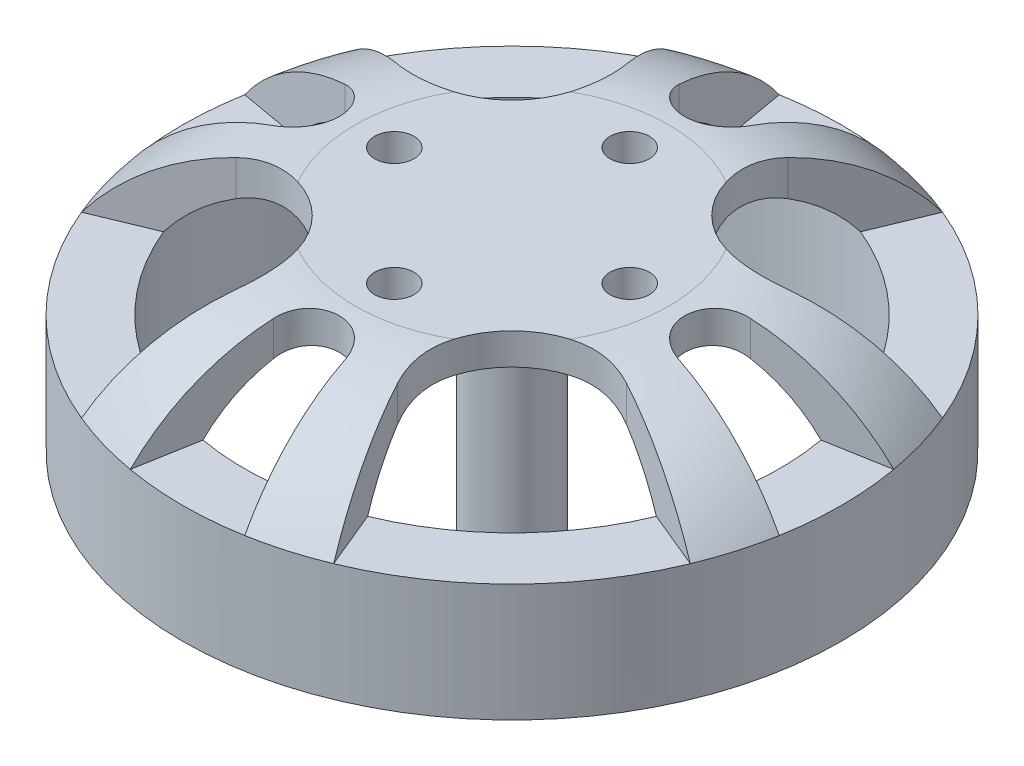
SolidWorks part; units mm, degrees
ref_plane "Front Plane" through (0, 0, 0) normal (0, 0, 1) x (1, 0, 0)
ref_plane "Top Plane" through (0, 0, 0) normal (0, 1, 0) x (1, 0, 0)
ref_plane "Right Plane" through (0, 0, 0) normal (1, 0, 0) x (0, 0, -1)
sketch "Sketch2" plane through (0, 0, 0) normal (0, 0, 1) x (1, 0, 0)
  line L0 (0, 0) -> (0, 19)
  line L1 (-21, 13.5) -> (-21, 6)
  line L2 (0, 19) -> (-10, 19)
  line L3 (0, 9.5) -> (-21, 9.5) construction
  line L4 (-21, 6) -> (-17, 6)
  line L5 (-17, 6) -> (-17, 13.5)
  line L6 (0, 0) -> (-2.5, 0)
  line L7 (-2.5, 0) -> (-2.5, 17)
  line L8 (-2.5, 17) -> (-10, 17)
  arc A0 (-10, 19) -> (-21, 13.5) centre (-10, 5.25) ccw
  arc A1 (-10, 17) -> (-17, 13.5) centre (-10, 8.25) ccw
  dimension "D1" = 21
  dimension "D2" = 19
  dimension "D3" = 7.5
  dimension "D4" = 10
  dimension "D5" = 4
  dimension "D6" = 2.5
  dimension "D7" = 2
  dimension "D8" = 4
revolve "Revolve2" add sketch "Sketch2" angle 360 about L0
hole_wizard "M3x0.5 Tapped Hole1" positions "Sketch4" profile "Sketch3" tap size "M3x0.5" standard "ANSI Metric" end condition up to next
sketch "Sketch4" plane through (0, 19, 0) normal (0, 1, 0) x (1, 0, 0)
  line L0 (0, 7.5) -> (0, -7.5) construction
  line L3 (-7.5, 0) -> (7.5, 0) construction
  point P0 (7.5, 0)
  point P2 (0, 7.5)
  point P4 (-7.5, 0)
  point P6 (0, -7.5)
  dimension "D1" = 15
sketch "Sketch3" plane through (7.5, 19, 0) normal (1, 0, 0) x (0, 0, 1)
  line L0 (0, 0) -> (0, 2)
  line L1 (0, 2) -> (1.25, 2)
  line L2 (1.25, 2) -> (1.25, 0)
  line L5 (1.25, 0) -> (0, 0)
  line L11 (0, -6.35) -> (0, 107.95) construction
  dimension "Thread Major Dia." = 2.5
  dimension "Thru Tap Drill Depth" = 2
sketch "Sketch6" plane through (0, 19, 0) normal (0, 1, 0) x (1, 0, 0)
  line L0 (0, 0) -> (21, 0) construction
  line L1 (0, 0) -> (0, 21) construction
  line L2 (12.9101, 2.2764) -> (20.681, 3.6466)
  line L3 (12.9101, -2.2764) -> (20.681, -3.6466)
  line L4 (0, 0) -> (14.8492, 14.8492) construction
  line L5 (8.0364, 19.4015) -> (5.1545, 12.4442)
  line L6 (19.4015, 8.0364) -> (12.4442, 5.1545)
  circle A0 centre (0, 0) radius 21 construction
  arc A1 (12.9101, 2.2764) -> (12.9101, -2.2764) centre (13.3115, 0) ccw
  arc A2 (20.681, 3.6466) -> (20.681, -3.6466) centre (0, 0) cw
  arc A3 (5.1545, 12.4442) -> (12.4442, 5.1545) centre (10.3091, 10.3091) ccw
  arc A4 (8.0364, 19.4015) -> (19.4015, 8.0364) centre (0, 0) cw
  point P11 (11, 0)
  point P18 (6.364, 6.364)
  dimension "D1" = 11
  dimension "D2" = 20
  dimension "D3" = 45
  dimension "D4" = 9
  dimension "D5" = 45
extrude "Cut-Extrude1" cut sketch "Sketch6" against normal blind 5.5
pattern_circular "CirPattern1" count 4 over 360 about axis through (0, 0, 0) along (0, 1, 0) of "Cut-Extrude1"
